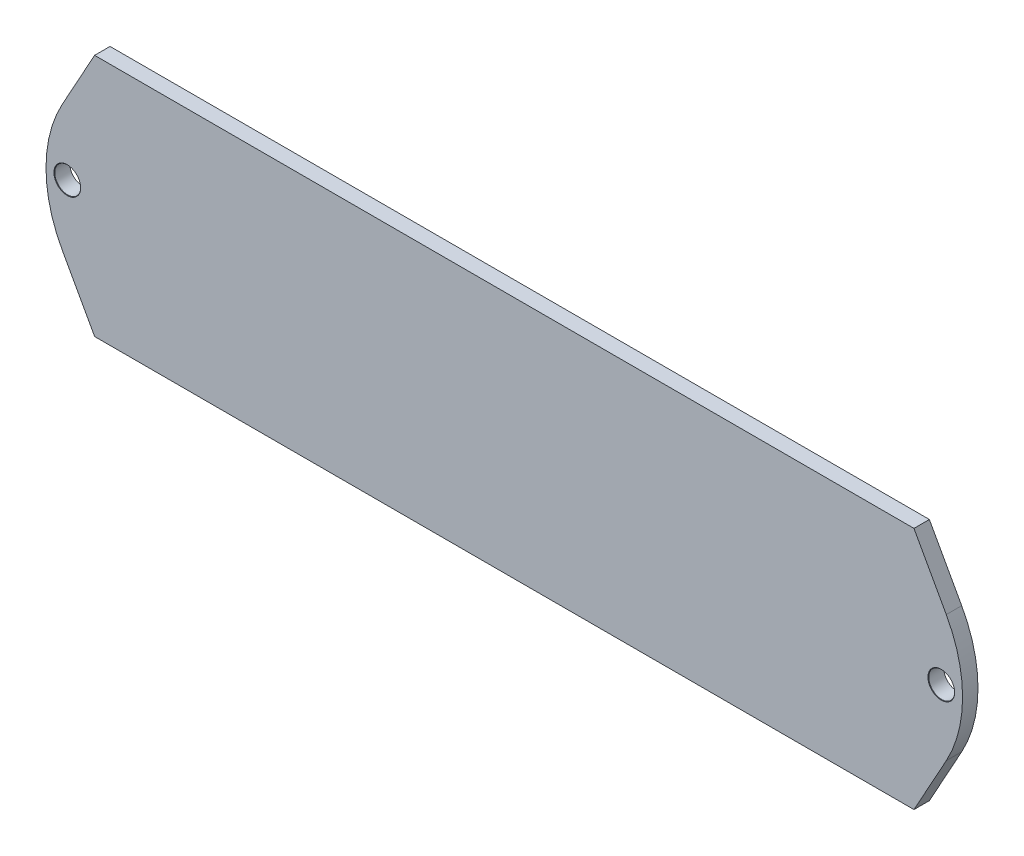
SolidWorks part; units mm, degrees
ref_plane "Front Plane" through (0, 0, 0) normal (0, 0, 1) x (1, 0, 0)
ref_plane "Top Plane" through (0, 0, 0) normal (0, 1, 0) x (1, 0, 0)
ref_plane "Right Plane" through (0, 0, 0) normal (1, 0, 0) x (0, 0, -1)
sketch "Sketch1" plane through (0, 0, 0) normal (0, 0, 1) x (1, 0, 0)
  line L10 (-50.6, 15.04) -> (50.6, 15.04)
  line L11 (50.6, 15.04) -> (54.5903, 7.8135)
  line L12 (54.5903, -7.8135) -> (50.6, -15.04)
  line L13 (50.6, -15.04) -> (-50.6, -15.04)
  line L14 (-50.6, -15.04) -> (-54.5903, -7.8135)
  line L15 (-54.5903, 7.8135) -> (-50.6, 15.04)
  line L16 (-50.6, 15.04) -> (-50.6, -15.04) construction
  line L18 (50.6, 15.04) -> (50.6, -15.04) construction
  arc A4 (54.5903, 7.8135) -> (54.5903, -7.8135) centre (40.44, 0) cw
  arc A5 (-54.5903, -7.8135) -> (-54.5903, 7.8135) centre (-40.44, 0) cw
  point P5 (0, 15.04)
  dimension "D1" = 10.16
  dimension "D3" = 8.255
  dimension "D4" = 101.2
  dimension "D5" = 30.08
extrude "Boss-Extrude1" add sketch "Sketch1" along normal blind 1.905
sketch "Sketch2" plane through (0, 0, 1.905) normal (0, 0, 1) x (1, 0, 0)
  line L0 (-53.975, 0) -> (53.975, 0) construction
  point P3 (0, 0)
  point P5 (-53.975, 0)
  point P6 (53.975, 0)
  dimension "D1" = 107.95
hole_wizard "Ø3.0mm Dowel Hole1" positions "Sketch2" profile "Sketch3" hole size "Ø3.0" standard "ANSI Metric" end condition through all
sketch "Sketch3" plane through (53.975, 0, 1.905) normal (1, 0, 0) x (0, -1, 0)
  line L0 (0, 0) -> (0, 1.905)
  line L1 (0, 1.905) -> (1.6, 1.905)
  line L2 (1.6, 1.905) -> (1.6, 0.05)
  line L3 (1.6, 0.05) -> (1.65, 0)
  line L5 (1.65, 0) -> (0, 0)
  line L6 (-1.6, 0.05) -> (-1.65, 0) construction
  line L11 (0, -6.35) -> (0, 107.95) construction
  dimension "Thru Hole Dia." = 3.2
  dimension "Thru Hole Depth" = 1.905
  dimension "Near C'Sink Dia." = 3.3
  dimension "Near C'Sink Angle" = 90
